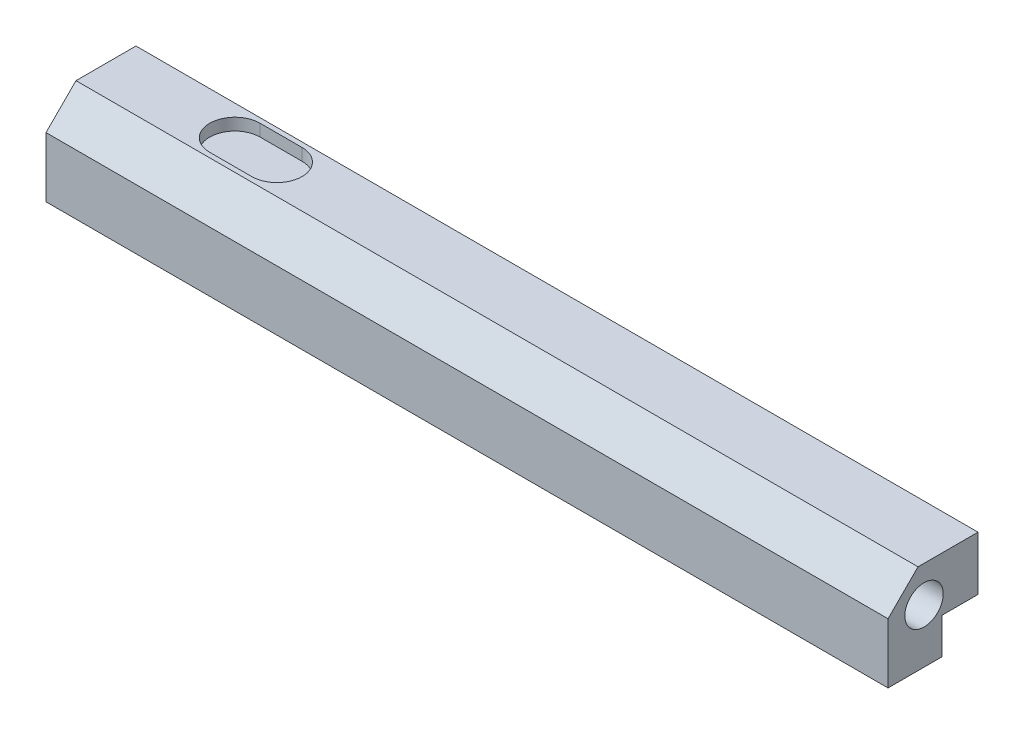
SolidWorks part; units mm, degrees
ref_plane "Plan de face" through (0, 0, 0) normal (0, 0, 1) x (1, 0, 0)
ref_plane "Plan de dessus" through (0, 0, 0) normal (0, 1, 0) x (1, 0, 0)
ref_plane "Plan de droite" through (0, 0, 0) normal (1, 0, 0) x (0, 0, -1)
sketch "Esquisse3" plane through (0, 0, 0) normal (1, 0, 0) x (0, 0, -1)
  line L0 (-4.5, -10.5) -> (-4.5, 4.5)
  line L1 (-4.5, 4.5) -> (10.5, 4.5)
  line L2 (10.5, 4.5) -> (10.5, -4.5)
  line L3 (10.5, -4.5) -> (4.5, -4.5)
  line L4 (4.5, -4.5) -> (4.5, -10.5)
  line L5 (4.5, -10.5) -> (-4.5, -10.5)
  line L6 (-4.5, 4.5) -> (4.5, -4.5) construction
  circle A1 centre (1.5, -1.5) radius 2.35
  point P8 (0, 0)
  dimension "D4" = 4.7
  dimension "D5" = 6
  dimension "D6" = 6
  dimension "D1" = 9
  dimension "D2" = 9
  dimension "D3" = 15
extrude "Boss.-Extru.2" add sketch "Esquisse3" along normal mid plane 140.4
chamfer "Chanfrein1" distance 5 angle 45 1 edges at (0, 4.5, 4.5)
sketch "Esquisse6" plane through (-70.2, 0, 0) normal (-1, 0, 0) x (0, 0, 1)
  circle A0 centre (-1.5, -1.5) radius 2.35 construction
  circle A1 centre (-1.5, -1.5) radius 2.35
  circle A2 centre (-1.5, -1.5) radius 3.2
  dimension "D1" = 6.4
extrude "Enlèv. mat.-Extru.1" cut sketch "Esquisse6" against normal blind 7
sketch "Esquisse7" plane through (70.2, 0, 0) normal (1, 0, 0) x (0, 0, -1)
  circle A0 centre (1.5, -1.5) radius 2.35 construction
  circle A1 centre (1.5, -1.5) radius 2.35
  circle A2 centre (1.5, -1.5) radius 3.2
  dimension "D1" = 6.4
extrude "Enlèv. mat.-Extru.2" cut sketch "Esquisse7" against normal blind 7
sketch "Esquisse8" plane through (0, 4.5, 0) normal (0, 1, 0) x (1, 0, 0)
  line L0 (-48.7, 5.5) -> (-41.7, 5.5) construction
  line L1 (-48.7, 9.7) -> (-41.7, 9.7)
  line L2 (-48.7, 1.3) -> (-41.7, 1.3)
  line L3 (-70.2, 5.5) -> (70.2, 5.5) construction
  line L4 (-70.2, 10.5) -> (-70.2, 0.5) construction
  line L5 (70.2, 10.5) -> (70.2, 0.5) construction
  arc A0 (-48.7, 9.7) -> (-48.7, 1.3) centre (-48.7, 5.5) ccw
  arc A1 (-41.7, 1.3) -> (-41.7, 9.7) centre (-41.7, 5.5) ccw
  point P2 (-45.2, 5.5)
  point P7 (-52.9, 5.5)
  point P8 (-37.5, 5.5)
  dimension "D1" = 8.4
  dimension "D2" = 15.4
  dimension "D3" = 25
extrude "Enlèv. mat.-Extru.3" cut sketch "Esquisse8" against normal blind 2
